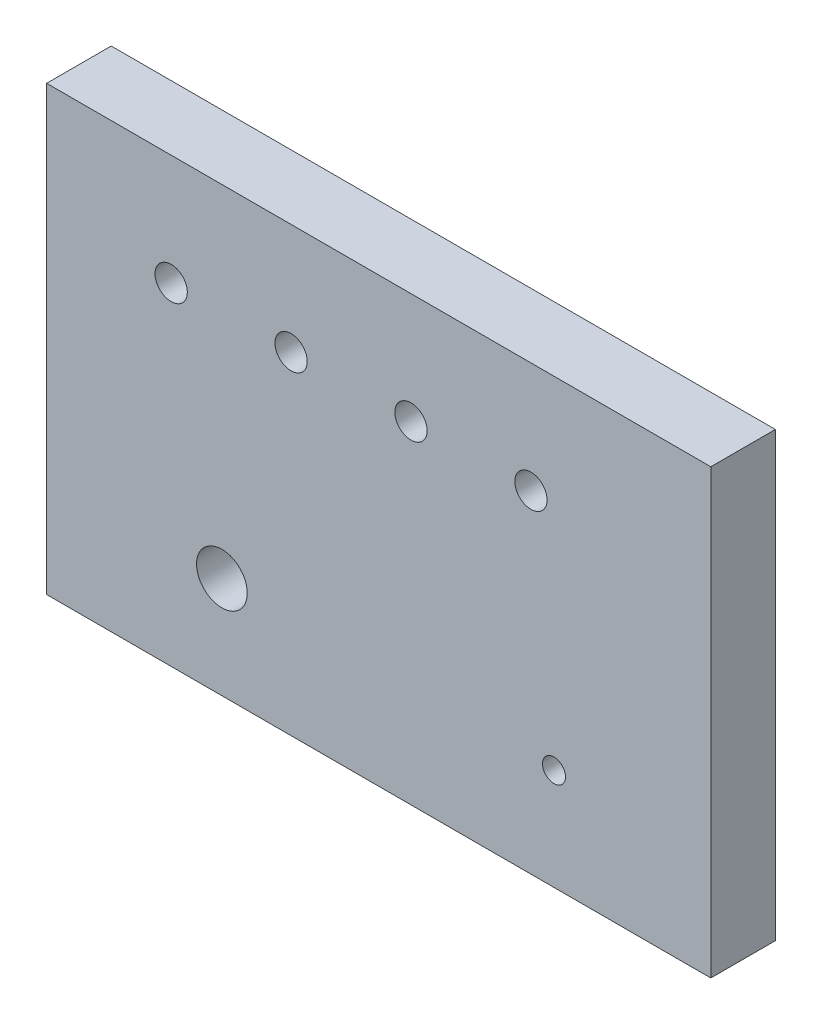
SolidWorks part; units mm, degrees
ref_plane "前视基准面" through (0, 0, 0) normal (0, 0, 1) x (1, 0, 0)
ref_plane "上视基准面" through (0, 0, 0) normal (0, 1, 0) x (1, 0, 0)
ref_plane "右视基准面" through (0, 0, 0) normal (1, 0, 0) x (0, 0, -1)
sketch "草图1" plane through (0, 0, 0) normal (0, 0, 1) x (1, 0, 0)
  line L1 (-72, 48) -> (72, 48)
  line L2 (-72, 48) -> (-72, -48)
  line L3 (-72, -48) -> (72, -48)
  line L4 (72, 48) -> (72, -48)
extrude "基底" add sketch "草图1" along normal blind 14
sketch "草图3" plane through (0, 0, 0) normal (0, 0, 1) x (1, 0, 0)
  circle A0 centre (-45, 24) radius 3.5
  dimension "D1" = 7
extrude "孔A" cut sketch "草图3" along normal through all
pattern_linear "阵列(线性)2" count 4 spacing 26 along (1, 0, 0) of "孔A"
sketch "草图4" plane through (0, 0, 0) normal (0, 0, 1) x (1, 0, 0)
  circle A0 centre (-34, -26) radius 5.5
  dimension "D1" = 11
extrude "孔B" cut sketch "草图4" along normal through all
sketch "草图5" plane through (0, 0, 0) normal (0, 0, 1) x (1, 0, 0)
  circle A0 centre (38, -26) radius 2.5
  dimension "D1" = 5
extrude "孔C" cut sketch "草图5" along normal through all
